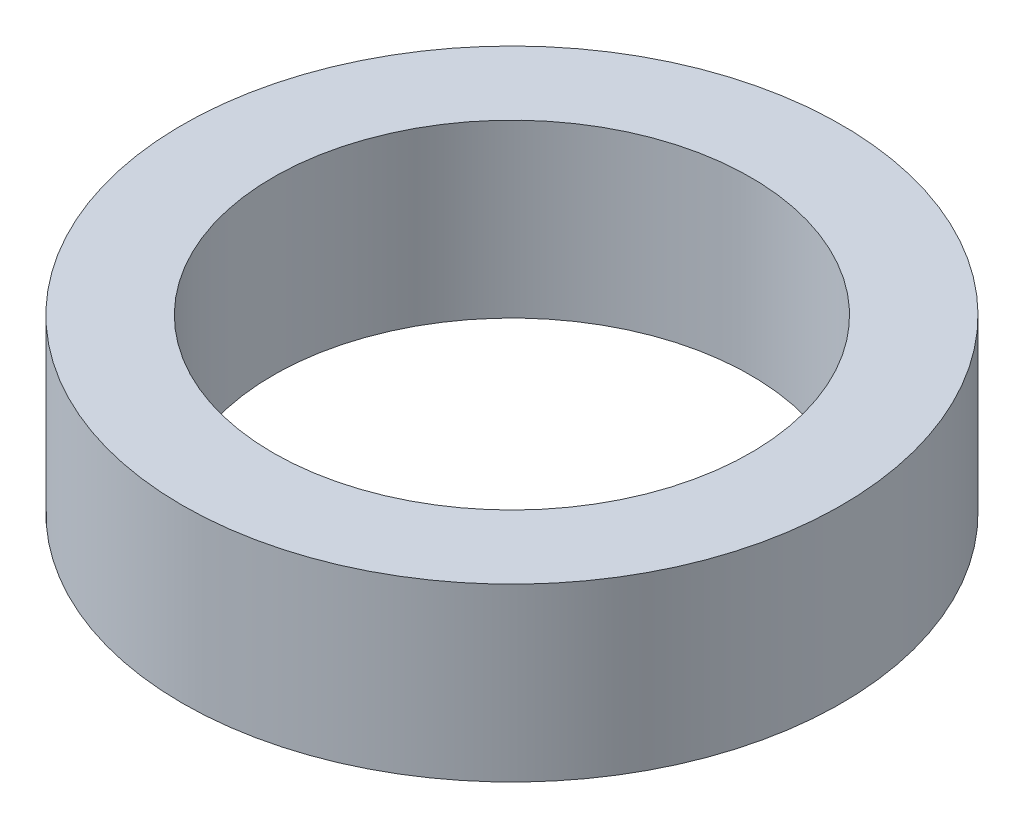
SolidWorks part; units mm, degrees
ref_plane "Front Plane" through (0, 0, 0) normal (0, 0, 1) x (1, 0, 0)
ref_plane "Top Plane" through (0, 0, 0) normal (0, 1, 0) x (1, 0, 0)
ref_plane "Right Plane" through (0, 0, 0) normal (1, 0, 0) x (0, 0, -1)
sketch "Sketch1" plane through (0, 0, 0) normal (0, 1, 0) x (1, 0, 0)
  circle A0 centre (0, 0) radius 317.5
  dimension "D1" = 635
extrude "Boss-Extrude1" add sketch "Sketch1" along normal blind 165.1
sketch "Sketch2" plane through (0, 165.1, 0) normal (0, 1, 0) x (1, 0, 0)
  circle A0 centre (0, 0) radius 230
  dimension "D1" = 460
extrude "Cut-Extrude1" cut sketch "Sketch2" against normal through all
